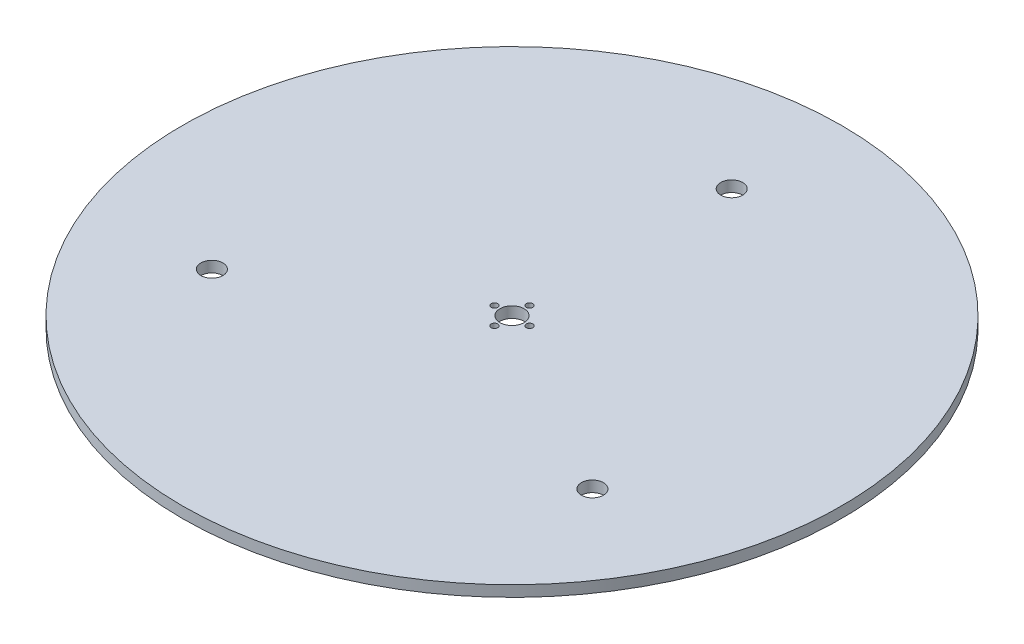
SolidWorks part; units mm, degrees
ref_plane "前视基准面" through (0, 0, 0) normal (0, 0, 1) x (1, 0, 0)
ref_plane "上视基准面" through (0, 0, 0) normal (0, 1, 0) x (1, 0, 0)
ref_plane "右视基准面" through (0, 0, 0) normal (1, 0, 0) x (0, 0, -1)
sketch "草图1" plane through (0, 0, 0) normal (0, 1, 0) x (1, 0, 0)
  line L0 (0, 100) -> (0, 0) construction
  line L1 (-86.6025, -50) -> (0, 0) construction
  line L2 (0, 0) -> (86.6025, -50) construction
  circle A0 centre (0, 0) radius 150
  circle A6 centre (0, 0) radius 100 construction
  circle A7 centre (0, 100) radius 5
  circle A8 centre (-86.6025, -50) radius 5
  circle A9 centre (86.6025, -50) radius 5
  circle A18 centre (-86.6025, -50) radius 25 construction
  circle A24 centre (0, 0) radius 8 construction
  circle A25 centre (0, 0) radius 5.5
  circle A26 centre (0, 8) radius 1.5
  circle A27 centre (8, 0) radius 1.5
  circle A28 centre (0, -8) radius 1.5
  circle A29 centre (-8, 0) radius 1.5
  point P24 (0, 0)
  point P25 (0, 0)
  point P35 (0, 0)
  dimension "D1" = 300
  dimension "D2" = 16
  dimension "D3" = 11
  dimension "D4" = 3
  dimension "D5" = 4
  dimension "D6" = 50
  dimension "D7" = 200
  dimension "D10" = 10
  dimension "D11" = 10
  dimension "D12" = 10
  dimension "D8" = 120
  dimension "D9" = 120
extrude "凸台-拉伸1" add sketch "草图1" along normal blind 5
